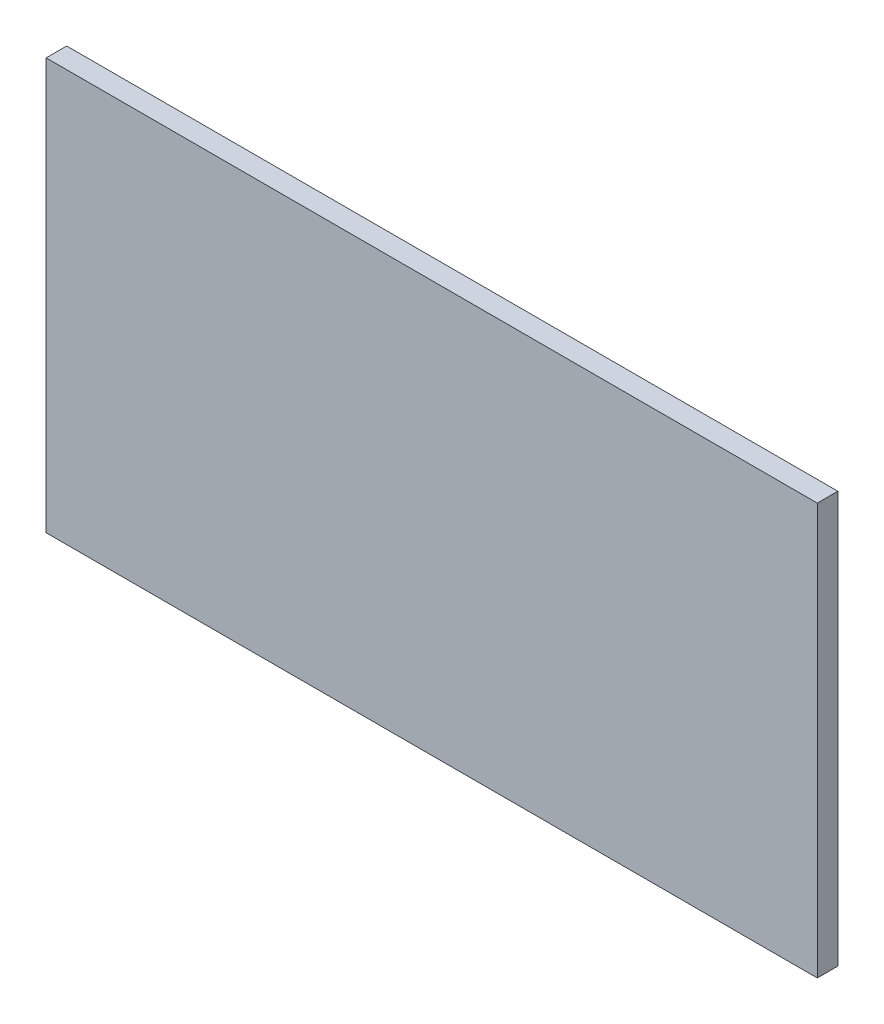
SolidWorks part; units mm, degrees
ref_plane "Front Plane" through (0, 0, 0) normal (0, 0, 1) x (1, 0, 0)
ref_plane "Top Plane" through (0, 0, 0) normal (0, 1, 0) x (1, 0, 0)
ref_plane "Right Plane" through (0, 0, 0) normal (1, 0, 0) x (0, 0, -1)
sketch "Sketch1" plane through (0, 0, 0) normal (1, 0, 0) x (0, 0, -1)
  line L1 (-2, -40) -> (2, -40)
  line L2 (-2, -40) -> (-2, 40)
  line L3 (-2, 40) -> (2, 40)
  line L4 (2, -40) -> (2, 40)
  line L5 (-2, -40) -> (2, 40) construction
  line L6 (-2, 40) -> (2, -40) construction
  point P0 (0, 0)
  dimension "D1" = 80
  dimension "D2" = 4
extrude "Boss-Extrude1" add sketch "Sketch1" along normal mid plane 150
